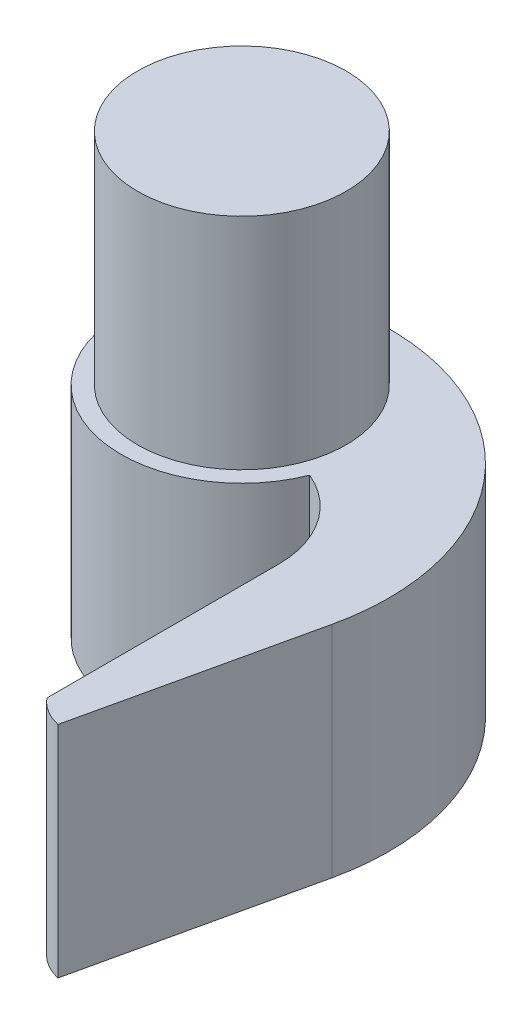
SolidWorks part; units mm, degrees
ref_plane "Front Plane" through (0, 0, 0) normal (0, 0, 1) x (1, 0, 0)
ref_plane "Top Plane" through (0, 0, 0) normal (0, 1, 0) x (1, 0, 0)
ref_plane "Right Plane" through (0, 0, 0) normal (1, 0, 0) x (0, 0, -1)
sketch "Sketch1" plane through (0, 0, 0) normal (0, 1, 0) x (1, 0, 0)
  line L0 (18.4245, -35.1774) -> (23.006, -14.8005)
  line L1 (15.8331, -33.5899) -> (15.8331, -12.488)
  arc A1 (0, 11) -> (10.2279, -4.0485) centre (0, 0) ccw
  arc A2 (23.006, -14.8005) -> (0, 11) centre (2.2654, -10.1373) ccw
  arc A3 (18.4245, -35.1774) -> (15.8331, -33.5899) centre (19.4579, -30.5814) cw
  arc A4 (15.8331, -12.488) -> (10.2279, -4.0485) centre (6.677, -12.488) ccw
  dimension "D1" = 22
  dimension "D2" = 21.2583
  dimension "D3" = 4.7107
  dimension "D4" = 9.156
  dimension "D5" = 2.2654
  dimension "D6" = 6.677
  dimension "D7" = 10.2279
  dimension "D8" = 18.4245
  dimension "D9" = 19.4579
extrude "Boss-Extrude1" add sketch "Sketch1" along normal blind 20
sketch "Sketch4" plane through (0, 20, 0) normal (0, 1, 0) x (1, 0, 0)
  circle A0 centre (0, 0) radius 9.5
  dimension "D1" = 19
extrude "Boss-Extrude2" add sketch "Sketch4" along normal blind 20
